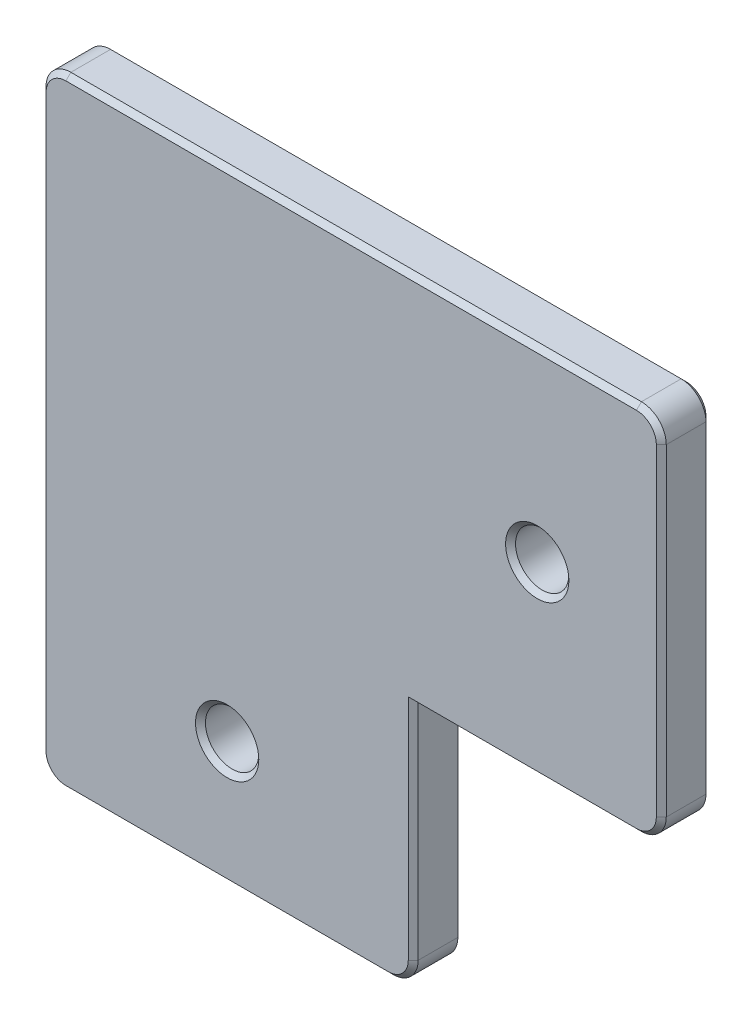
SolidWorks part; units mm, degrees
ref_plane "Front Plane" through (0, 0, 0) normal (0, 0, 1) x (1, 0, 0)
ref_plane "Top Plane" through (0, 0, 0) normal (0, 1, 0) x (1, 0, 0)
ref_plane "Right Plane" through (0, 0, 0) normal (1, 0, 0) x (0, 0, -1)
sketch "Sketch1" plane through (0, 0, 0) normal (0, 0, 1) x (1, 0, 0)
  line L1 (0, -50) -> (30, -50)
  line L2 (30, -50) -> (30, -30)
  line L3 (30, -30) -> (50, -30)
  line L4 (50, -30) -> (50, 0)
  line L5 (50, 0) -> (0, 0)
  line L7 (0, -50) -> (0, 0)
  line L8 (0, 0) -> (30, -30) construction
  line L9 (40, -30) -> (40, 0) construction
  line L10 (30, -40) -> (0, -40) construction
  circle A0 centre (15, -40) radius 2.15
  circle A1 centre (40, -15) radius 2.15
  point P14 (10, -40)
  dimension "D5" = 4.3
  dimension "D1" = 20
  dimension "D2" = 20
  dimension "D3" = 45
  dimension "D4" = 30
extrude "Boss-Extrude1" add sketch "Sketch1" along normal blind 4
fillet "Fillet1" radius 2 5 edges at (0, 0, 2) (50, 0, 2) (50, -30, 2) (0, -50, 2) (30, -50, 2)
chamfer "Chamfer1" distance 0.4 angle 45 26 edges at (42.15, -15, 4) (49.4142, -0.5858, 4) (50, -15, 4) (49.4142, -29.4142, 4) (39, -30, 4) (30, -39, 4) (29.4142, -49.4142, 4) (15, -50, 4) (0.5858, -49.4142, 4) (0, -25, 4) (0.5858, -0.5858, 4) (25, 0, 4) (17.15, -40, 4) (42.15, -15, 0) (17.15, -40, 0) (0.5858, -49.4142, 0) (15, -50, 0) (29.4142, -49.4142, 0) (30, -39, 0) (39, -30, 0) (49.4142, -29.4142, 0) (50, -15, 0) (49.4142, -0.5858, 0) (25, 0, 0) (0.5858, -0.5858, 0) (0, -25, 0)
